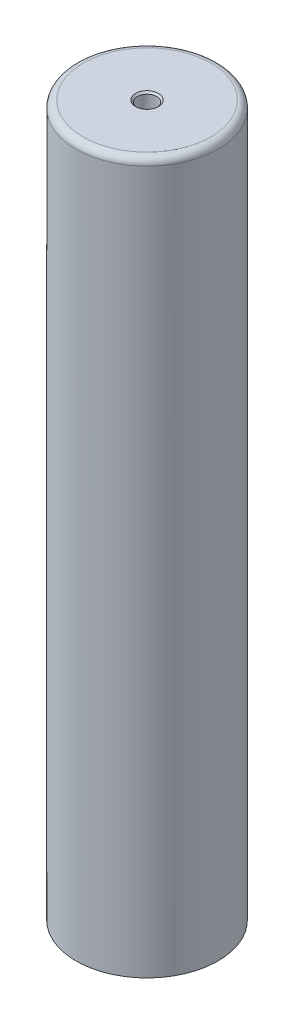
SolidWorks part; units mm, degrees
ref_plane "Front Plane" through (0, 0, 0) normal (0, 0, 1) x (1, 0, 0)
ref_plane "Top Plane" through (0, 0, 0) normal (0, 1, 0) x (1, 0, 0)
ref_plane "Right Plane" through (0, 0, 0) normal (1, 0, 0) x (0, 0, -1)
sketch "Sketch1" plane through (0, 0, 0) normal (0, 0, 1) x (1, 0, 0)
  line L0 (0, 0) -> (0, 314.9411) construction
  line L1 (0, 250) -> (25, 250)
  line L2 (25, 250) -> (25, 0)
  line L3 (25, 0) -> (0, 0)
  line L4 (0, 0) -> (0, 250)
  point P6 (0, 314.9411)
  dimension "D1" = 50
  dimension "D2" = 250
revolve "Revolve1" add sketch "Sketch1" angle 360 about L0
sketch "Sketch2" plane through (0, 250, 0) normal (0, 1, 0) x (1, 0, 0)
  point P0 (0, 0)
hole_wizard "M8 Tapped Hole1" positions "3DSketch1" profile "Sketch3" tap size "M8" standard "ISO"
sketch3d "3DSketch1"
  point P0 (0, 250, 0)
sketch "Sketch3" plane through (0, 250, 0) normal (1, 0, 0) x (0, 0, 1)
  line L0 (0, 0) -> (0, 18.7929)
  line L1 (0, 18.7929) -> (3.4, 16.75)
  line L2 (3.4, 16.75) -> (3.4, 0.625)
  line L3 (3.4, 0.625) -> (4.025, 0)
  line L5 (4.025, 0) -> (0, 0)
  line L6 (-3.4, 0.625) -> (-4.025, 0) construction
  line L10 (0, 18.7929) -> (-3.4, 16.75) construction
  line L11 (0, -6.35) -> (0, 107.95) construction
  dimension "Tap Drill Dia." = 6.8
  dimension "Tap Drill Depth" = 16.75
  dimension "Near C'Sink Dia." = 8.05
  dimension "Near C'Sink Angle" = 90
  dimension "Drill Angle" = 118
cosmetic thread "Hole Thread1" parameters "D1"=13, "D2"=8
fillet "Fillet1" radius 2.5 1 edges at (0, 250, -25)
